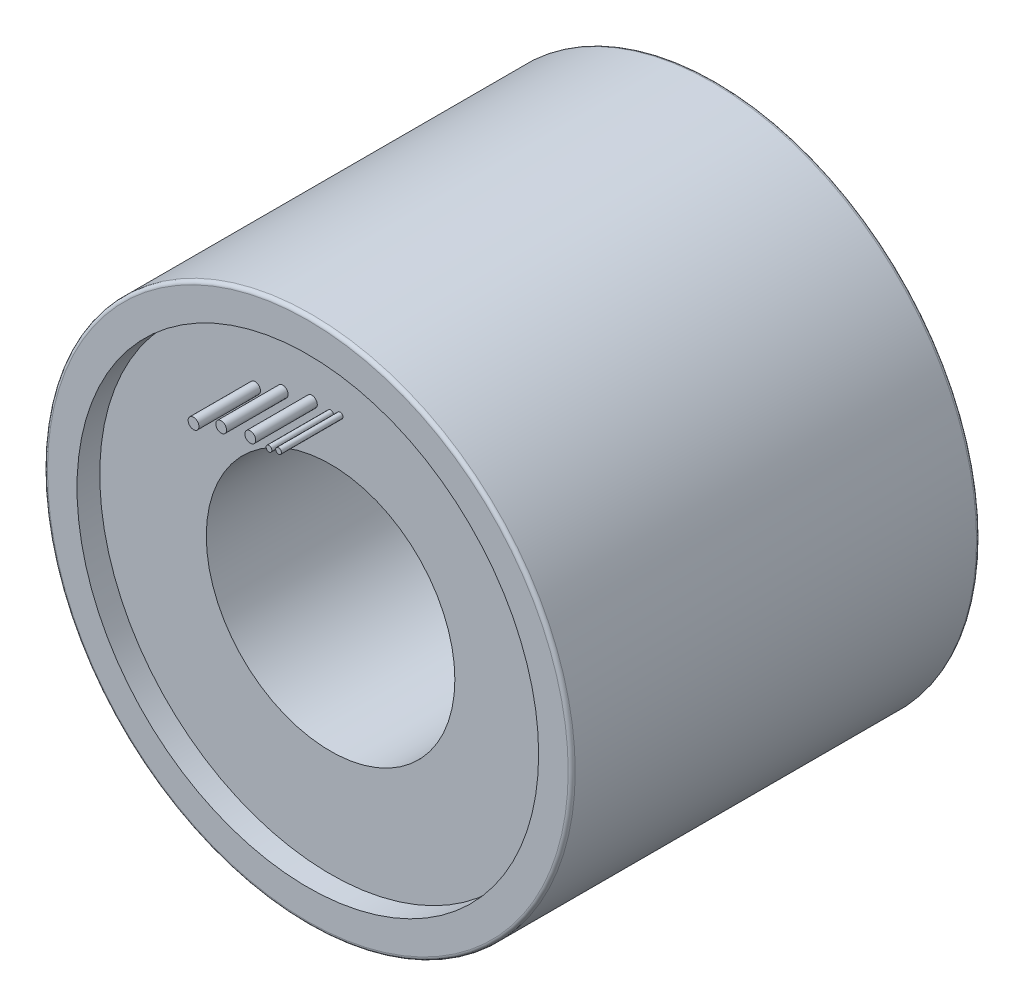
SolidWorks part; units mm, degrees
ref_plane "前视基准面" through (0, 0, 0) normal (0, 0, 1) x (1, 0, 0)
ref_plane "上视基准面" through (0, 0, 0) normal (0, 1, 0) x (1, 0, 0)
ref_plane "右视基准面" through (0, 0, 0) normal (1, 0, 0) x (0, 0, -1)
sketch "草图1" plane through (0, 0, 0) normal (0, 0, 1) x (1, 0, 0)
  circle A0 centre (0, 0) radius 37.4815
  dimension "D1" = 74.963
extrude "凸台-拉伸1" add sketch "草图1" along normal blind 58
sketch "草图2" plane through (0, 0, 0) normal (0, 0, -1) x (-1, 0, 0)
  circle A0 centre (0, 0) radius 32.785
  dimension "D1" = 65.57
extrude "切除-拉伸1" cut sketch "草图2" against normal blind 0.5 contours A0
sketch "草图3" plane through (0, 0, 58) normal (0, 0, 1) x (1, 0, 0)
  circle A0 centre (0, 0) radius 32.785
  dimension "D1" = 65.57
extrude "切除-拉伸2" cut sketch "草图3" against normal blind 3.23
sketch "草图4" plane through (0, 0, 0.5) normal (0, 0, -1) x (-1, 0, 0)
  circle A0 centre (0, 0) radius 17.655
  dimension "D1" = 35.31
extrude "切除-拉伸3" cut sketch "草图4" against normal through all
sketch "草图5" plane through (0, 0, 54.77) normal (0, 0, 1) x (1, 0, 0)
  line L0 (0, 0) -> (0, 42.0559) construction
  line L1 (0, 0) -> (2.4494, 43.9484) construction
  line L2 (0, 0) -> (-4.5346, 41.1393) construction
  line L3 (0, 0) -> (-12.565, 42.9967) construction
  line L4 (0, 0) -> (-21.5051, 43.5313) construction
  circle A0 centre (0, 0) radius 23.9425 construction
  circle A1 centre (0, 0) radius 24.377 construction
  circle A2 centre (0, 0) radius 24.1935 construction
  circle A3 centre (-10.7157, 21.691) radius 0.766
  circle A4 centre (-6.7863, 23.2222) radius 0.766
  circle A5 centre (-2.6507, 24.0479) radius 0.766
  circle A6 centre (0, 23.9425) radius 0.4065
  circle A7 centre (1.3565, 24.3392) radius 0.4065
  dimension "D5" = 47.885
  dimension "D6" = 48.754
  dimension "D7" = 48.387
  dimension "D8" = 1.532
  dimension "D9" = 1.532
  dimension "D10" = 1.532
  dimension "D11" = 0.813
  dimension "D12" = 0.813
  dimension "D1" = 6.29
  dimension "D2" = 10
  dimension "D3" = 10
  dimension "D4" = 3.19
extrude "凸台-拉伸2" add sketch "草图5" along normal blind 8.75
fillet "圆角1" radius 0.5 2 edges at (37.4815, 0, 58) (37.4815, 0, 0)
